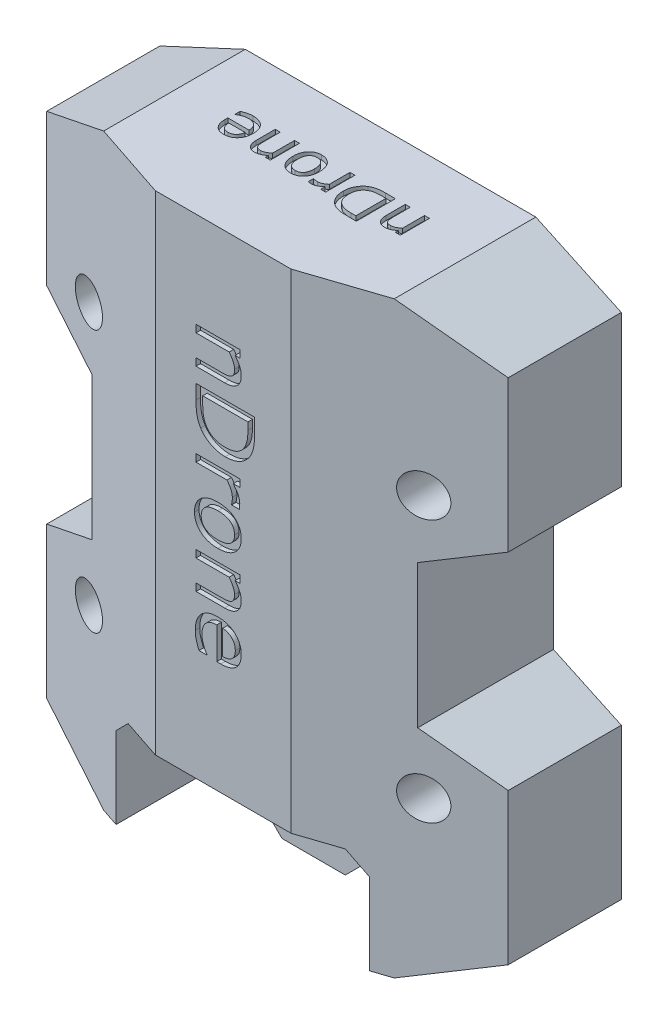
SolidWorks part; units mm, degrees
material "ABS"
ref_plane "Plano frontal" through (0, 0, 0) normal (0, 0, 1) x (1, 0, 0)
ref_plane "Plano superior" through (0, 0, 0) normal (0, 1, 0) x (1, 0, 0)
ref_plane "Plano direito" through (0, 0, 0) normal (1, 0, 0) x (0, 0, -1)
sketch "Esboço1" plane through (0, 0, 0) normal (0, 0, 1) x (1, 0, 0)
  line L11 (0, 0) -> (0, 32.5) construction
  line L12 (0, 0) -> (-18, 0) construction
  line L13 (16.0546, 32.5) -> (-16.0546, 32.5)
  line L14 (-16.0546, 32.5) -> (-25.5, 28.0922)
  line L15 (-25.5, 28.0922) -> (-25.5, 11.4078)
  line L16 (-25.5, 11.4078) -> (-18, 7.9078)
  line L17 (-18, 7.9078) -> (-18, -7.9078)
  line L18 (-18, -7.9078) -> (-25.5, -11.4078)
  line L19 (-25.5, -11.4078) -> (-25.5, -28.0922)
  line L20 (-25.5, -28.0922) -> (-16.0546, -32.5)
  line L21 (-16.0546, -32.5) -> (16.0546, -32.5)
  line L22 (16.0546, -32.5) -> (25.5, -28.0922)
  line L23 (25.5, -11.4078) -> (18, -7.9078)
  line L24 (18, -7.9078) -> (18, 7.9078)
  line L25 (18, 7.9078) -> (25.5, 11.4078)
  line L26 (25.5, 11.4078) -> (25.5, 28.0922)
  line L27 (25.5, 28.0922) -> (16.0546, 32.5)
  line L28 (25.5, -28.0922) -> (25.5, -11.4078)
  point P0 (0, 0)
  dimension "D3" = 32.5
  dimension "D4" = 18
  dimension "D5" = 18
  dimension "D7" = 25.5
  dimension "D1" = 15.8157
  dimension "D2" = 32.5
  dimension "D6" = 25.5
  dimension "D8" = 25.5
  dimension "D9" = 25.5
  dimension "D10" = 32.1092
  dimension "D11" = 15.8157
  dimension "D12" = 32.1092
  dimension "D13" = 154.983
  dimension "D14" = 154.983
  dimension "D15" = 154.983
  dimension "D16" = 154.983
  dimension "D17" = 115.017
  dimension "D18" = 115.017
  dimension "D19" = 115.017
  dimension "D20" = 115.017
  dimension "D21" = 0
  dimension "D22" = 0
extrude "Ressalto-extrusão1" add sketch "Esboço1" along normal blind 18.5
sketch "Esboço4" plane through (0, 0, 18.5) normal (0, 0, 1) x (1, 0, 0)
  line L0 (-16.0546, -32.5) -> (16.0546, -32.5) construction
  line L5 (-14, -32.5) -> (14, -32.5)
  line L6 (-14, -32.5) -> (-14, -21.5)
  line L7 (-14, -21.5) -> (14, -21.5)
  line L8 (14, -32.5) -> (14, -21.5)
  dimension "D1" = 11
  dimension "D2" = 14
  dimension "D3" = 14
extrude "Corte-extrusão1" cut sketch "Esboço4" against normal blind 10
sketch "Esboço5" plane through (0, 0, 8.5) normal (0, 0, 1) x (1, 0, 0)
  line L0 (14, -21.5) -> (-14, -21.5) construction
  line L1 (-14, -32.5) -> (-5.5, -32.5)
  line L2 (-14, -32.5) -> (-14, -21.5)
  line L3 (-14, -21.5) -> (-5.5, -21.5)
  line L4 (-5.5, -32.5) -> (-5.5, -21.5)
  line L5 (0, -21.5) -> (0, -32.5) construction
  line L6 (14, -21.5) -> (-14, -21.5) construction
  line L7 (-14, -32.5) -> (14, -32.5) construction
  line L8 (5.5, -32.5) -> (5.5, -21.5)
  line L9 (14, -21.5) -> (5.5, -21.5)
  line L10 (14, -32.5) -> (14, -21.5)
  line L11 (14, -32.5) -> (5.5, -32.5)
  dimension "D1" = 8.5
extrude "Corte-extrusão2" cut sketch "Esboço5" against normal blind 3.6
chamfer "Chanfro6" distance 2 angle 45 6 edges at (14, -21.5, 11.7) (-14, -21.5, 11.7) (5.5, -21.5, 6.7) (-5.5, -21.5, 6.7) (5.5, -32.5, 6.7) (-5.5, -32.5, 6.7)
sketch "Esboço6" plane through (0, 32.5, 0) normal (0, 1, 0) x (1, 0, 0)
  line L0 (0, 0) -> (0, -18.5) construction
  line L1 (16.0546, -18.5) -> (-16.0546, -18.5) construction
  line L2 (-7.5, -18.5) -> (-25.5, -12.5)
  line L3 (-25.5, -18.5) -> (-25.5, 0) construction
  line L4 (-25.5, -12.5) -> (-25.5, -18.5)
  line L5 (-25.5, -18.5) -> (-7.5, -18.5)
  line L9 (16.0546, 0) -> (-16.0546, 0) construction
  line L10 (25.5, -18.5) -> (7.5, -18.5)
  line L11 (25.5, -12.5) -> (25.5, -18.5)
  line L12 (7.5, -18.5) -> (25.5, -12.5)
  dimension "D1" = 6
  dimension "D2" = 18
extrude "Corte-extrusão3" cut sketch "Esboço6" against normal through all and the other way through all
shell "Casca1" thickness 1.5
sketch "Esboço7" plane through (0, 0, 8.5) normal (0, 0, 1) x (1, 0, 0)
  line L1 (-3.75, -28.69) -> (3.75, -28.69)
  line L2 (-3.75, -28.69) -> (-3.75, -21.19)
  line L3 (-3.75, -21.19) -> (3.75, -21.19)
  line L4 (3.75, -28.69) -> (3.75, -21.19)
  line L5 (-3.75, -28.69) -> (3.75, -21.19) construction
  line L6 (-3.75, -21.19) -> (3.75, -28.69) construction
  point P0 (0, -24.94)
  dimension "D1" = 7.5
  dimension "D2" = 7.5
  dimension "D3" = 0
  dimension "D4" = 24.94
extrude "Corte-extrusão4" cut sketch "Esboço7" against normal through all
sketch "Esboço8" plane through (0, 0, 4.9) normal (0, 0, 1) x (1, 0, 0)
  line L0 (14, -32.5) -> (14, -23.5) construction
  line L1 (6, -28.395) -> (14, -28.395)
  line L2 (6, -28.395) -> (6, -22.395)
  line L3 (6, -22.395) -> (14, -22.395)
  line L4 (14, -28.395) -> (14, -22.395)
  line L5 (6, -28.395) -> (14, -22.395) construction
  line L6 (6, -22.395) -> (14, -28.395) construction
  line L7 (3.75, -28.69) -> (3.75, -21.5) construction
  point P0 (10, -25.395)
  point P9 (3.75, -25.095)
  dimension "D1" = 8
  dimension "D2" = 6
  dimension "D3" = 4
  dimension "D4" = 0.3
extrude "Corte-extrusão5" cut sketch "Esboço8" against normal through all
sketch "Esboço9" plane through (0, 0, 4.9) normal (0, 0, 1) x (1, 0, 0)
  line L0 (3.75, -21.19) -> (-3.75, -21.19) construction
  line L1 (-3.75, -21.5) -> (-3.75, -28.69) construction
  circle A0 centre (-10, -25.095) radius 1.75
  point P4 (0, -21.19)
  point P7 (-3.75, -25.095)
  dimension "D1" = 10
  dimension "D2" = 0
  dimension "D3" = 3.5
extrude "Corte-extrusão6" cut sketch "Esboço9" against normal through all
sketch "Esboço11" plane through (0, 0, 0) normal (0, 0, -1) x (-1, 0, 0)
  line L3 (-18, 0) -> (18, 0) construction
  line L4 (-18, -7.9078) -> (-18, 7.9078) construction
  line L5 (18, 7.9078) -> (18, -7.9078) construction
  circle A0 centre (-18.5, 14.5) radius 2.5
  circle A1 centre (-18.5, -14.5) radius 2.5
  dimension "D1" = 18.5
  dimension "D2" = 14.5
  dimension "D3" = 5
extrude "Ressalto-extrusão2" add sketch "Esboço11" against normal up to surface (22.5022 mm away) from offset 2.25 offset against normal yes
sketch "Esboço13" plane through (0, 0, 2.25) normal (0, 0, -1) x (-1, 0, 0)
  circle A0 centre (-18.5, 14.5) radius 1.25
  circle A1 centre (-18.5, -14.5) radius 1.25
  dimension "D1" = 2.5
  dimension "D2" = 2.5
extrude "Corte-extrusão8" cut sketch "Esboço13" against normal through all
sketch "Esboço14" plane through (0, 0, 2.25) normal (0, 0, -1) x (-1, 0, 0)
  line L0 (-18.5, 17.5) -> (-24, 17.5)
  line L1 (-24, 12.3631) -> (-24, 27.1369) construction
  line L2 (-24, 17.5) -> (-24, 12.3631)
  line L5 (-24, 12.3631) -> (-16.5, 8.8631)
  line L7 (-16.5, 8.8631) -> (-15.5509, 13.9497)
  line L8 (-18, 0) -> (18, 0) construction
  line L9 (-18, -7.9078) -> (-18, 7.9078) construction
  line L10 (18, 7.9078) -> (18, -7.9078) construction
  line L11 (-16.5, -8.8631) -> (-15.5509, -13.9497)
  line L12 (-24, -12.3631) -> (-16.5, -8.8631)
  line L13 (-24, -17.5) -> (-24, -12.3631)
  line L14 (-18.5, -17.5) -> (-24, -17.5)
  arc A0 (-15.5509, 13.9497) -> (-18.5, 17.5) centre (-18.5, 14.5) ccw
  arc A1 (-15.5509, -13.9497) -> (-18.5, -17.5) centre (-18.5, -14.5) cw
  circle A2 centre (-18.5, 14.5) radius 1.25
  circle A3 centre (-18.5, -14.5) radius 1.25
  dimension "D1" = 6
extrude "Ressalto-extrusão3" add sketch "Esboço14" against normal up to surface (17.6689 mm away) from offset 5 offset against normal yes
sketch "Esboço15" plane through (0, 0, 7.25) normal (0, 0, -1) x (-1, 0, 0)
  line L0 (-18, 0) -> (18, 0) construction
  line L1 (-18, -7.9078) -> (-18, 7.9078) construction
  line L2 (18, 7.9078) -> (18, -7.9078) construction
  circle A0 centre (-18.5, 14.5) radius 2.25
  circle A1 centre (-18.5, -14.5) radius 2.25
  dimension "D1" = 4.5
extrude "Corte-extrusão9" cut sketch "Esboço15" against normal through all from offset 2 offset against normal yes
mirror "Espelhar10" about plane through (0, 0, 0) normal (1, 0, 0) of "Corte-extrusão9", "Ressalto-extrusão3", "Corte-extrusão8", "Ressalto-extrusão2"
sketch "Esboço19" plane through (-6.3, 0, 18.9) normal (-0.3162, 0, 0.9487) x (0.9487, 0, 0.3162)
  line L1 (-20.2386, 28.0922) -> (-4.6705, 28.0922)
  line L2 (-20.2386, 28.0922) -> (-20.2386, -26.9969)
  line L3 (-20.2386, -26.9969) -> (-4.6705, -26.9969)
  line L4 (-4.6705, 28.0922) -> (-4.6705, -26.9969)
extrude "Corte-extrusão10" cut sketch "Esboço19" along normal through all
sketch "Esboço20" plane through (0, 0, 18.5) normal (0, 0, 1) x (1, 0, 0)
  line L0 (-3, 33.5952) -> (-3, -20.4048) construction
  line L4 (-7.5, -21.5) -> (-7.5, 32.5) construction
  dimension "D1" = 4.5
sketch "Esboço21" plane through (0, 0, 18.5) normal (0, 0, 1) x (1, 0, 0)
  text T0 "nDrone" font "Verdana" height in points 24
extrude "Corte-extrusão11" cut sketch "Esboço21" against normal blind 0.5
sketch "Esboço23" plane through (0, 32.5, 0) normal (0, 1, 0) x (1, 0, 0)
  line L0 (-15.9938, -6) -> (16.1154, -6) construction
  line L3 (16.0546, 0) -> (-16.0546, 0) construction
  dimension "D1" = 6
sketch "Esboço24" plane through (0, 32.5, 0) normal (0, 1, 0) x (1, 0, 0)
  text T0 "nDrone" font "Verdana" height in points 16
extrude "Corte-extrusão12" cut sketch "Esboço24" against normal blind 0.5
sketch "Esboço26" plane through (0, 0, 0) normal (0, 0, -1) x (-1, 0, 0)
  line L222 (-24, 27.1369) -> (-15.7218, 31)
  line L223 (-15.7218, 31) -> (15.7218, 31)
  line L224 (15.7218, 31) -> (24, 27.1369)
  line L225 (24, 27.1369) -> (24, 12.3631)
  line L226 (24, 12.3631) -> (16.5, 8.8631)
  line L227 (16.5, 8.8631) -> (16.5, -8.8631)
  line L228 (16.5, -8.8631) -> (24, -12.3631)
  line L229 (24, -12.3631) -> (24, -27.1369)
  line L230 (24, -27.1369) -> (15.7218, -31)
  line L231 (15.7218, -31) -> (-15.7218, -31)
  line L232 (-15.7218, -31) -> (-24, -27.1369)
  line L233 (-24, -27.1369) -> (-24, -12.3631)
  line L234 (-24, -12.3631) -> (-16.5, -8.8631)
  line L235 (-16.5, -8.8631) -> (-16.5, 8.8631)
  line L236 (-16.5, 8.8631) -> (-24, 12.3631)
  line L237 (-24, 12.3631) -> (-24, 27.1369)
  line L238 (-24.7, 27.5827) -> (-15.8771, 31.7)
  line L239 (-15.8771, 31.7) -> (15.8771, 31.7)
  line L240 (15.8771, 31.7) -> (24.7, 27.5827)
  line L241 (24.7, 27.5827) -> (24.7, 11.9173)
  line L242 (24.7, 11.9173) -> (17.2, 8.4173)
  line L243 (17.2, 8.4173) -> (17.2, -8.4173)
  line L244 (17.2, -8.4173) -> (24.7, -11.9173)
  line L245 (24.7, -11.9173) -> (24.7, -27.5827)
  line L246 (24.7, -27.5827) -> (15.8771, -31.7)
  line L247 (15.8771, -31.7) -> (-15.8771, -31.7)
  line L248 (-15.8771, -31.7) -> (-24.7, -27.5827)
  line L249 (-24.7, -27.5827) -> (-24.7, -11.9173)
  line L250 (-24.7, -11.9173) -> (-17.2, -8.4173)
  line L251 (-17.2, -8.4173) -> (-17.2, 8.4173)
  line L252 (-17.2, 8.4173) -> (-24.7, 11.9173)
  line L253 (-24.7, 11.9173) -> (-24.7, 27.5827)
  dimension "D1" = 0.7
extrude "Corte-extrusão13" cut sketch "Esboço26" against normal blind 2.1
